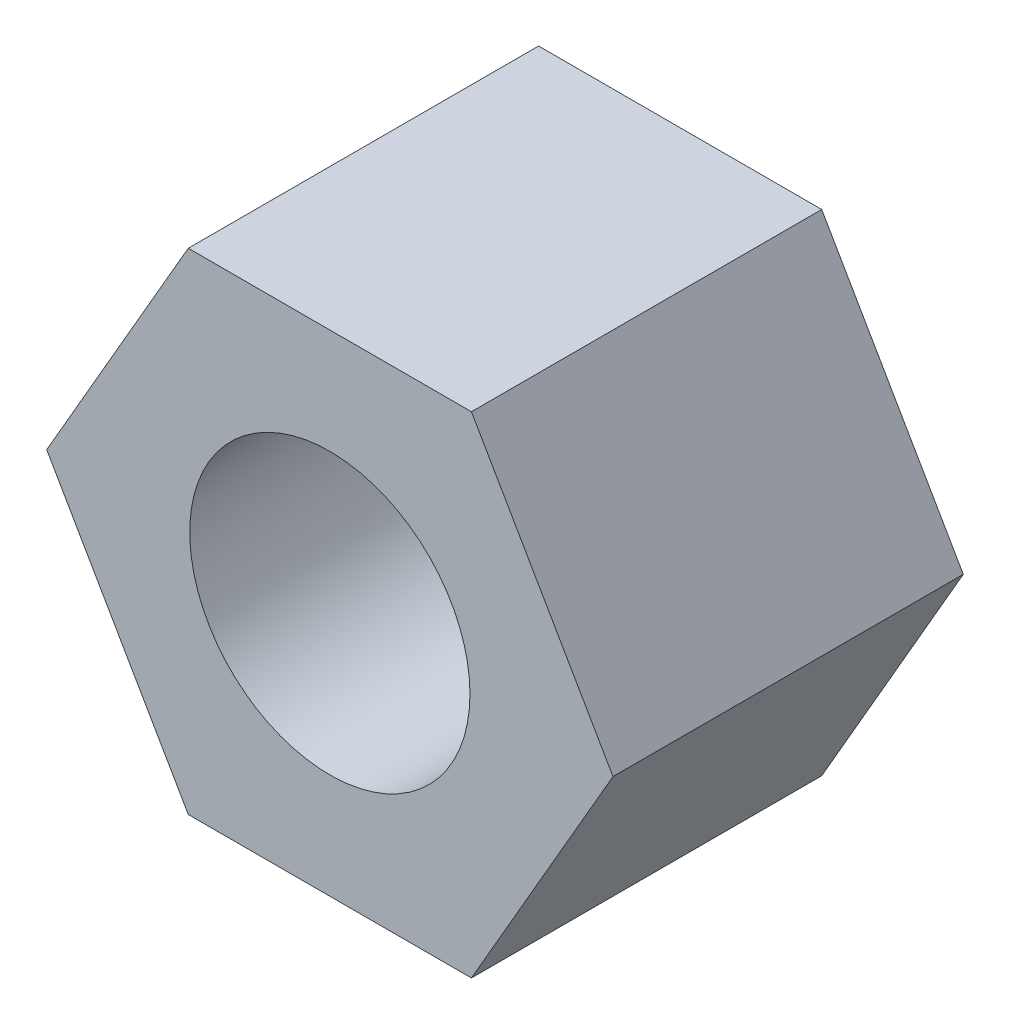
SolidWorks part; units mm, degrees
ref_plane "Front Plane" through (0, 0, 0) normal (0, 0, 1) x (1, 0, 0)
ref_plane "Top Plane" through (0, 0, 0) normal (0, 1, 0) x (1, 0, 0)
ref_plane "Right Plane" through (0, 0, 0) normal (1, 0, 0) x (0, 0, -1)
sketch "Across_flats_7" plane through (0, 0, 0) normal (0, 0, 1) x (1, 0, 0)
  line L0 (4.0415, 0) -> (2.0207, 3.5)
  line L1 (2.0207, 3.5) -> (-2.0207, 3.5)
  line L2 (-2.0207, 3.5) -> (-4.0415, 0)
  line L3 (-4.0415, 0) -> (-2.0207, -3.5)
  line L4 (-2.0207, -3.5) -> (2.0207, -3.5)
  line L5 (2.0207, -3.5) -> (4.0415, 0)
  circle A0 centre (0, 0) radius 2
  dimension "D1" = 4
extrude "Nut_thread_envelope_height_5" add sketch "Across_flats_7" along normal blind 5
